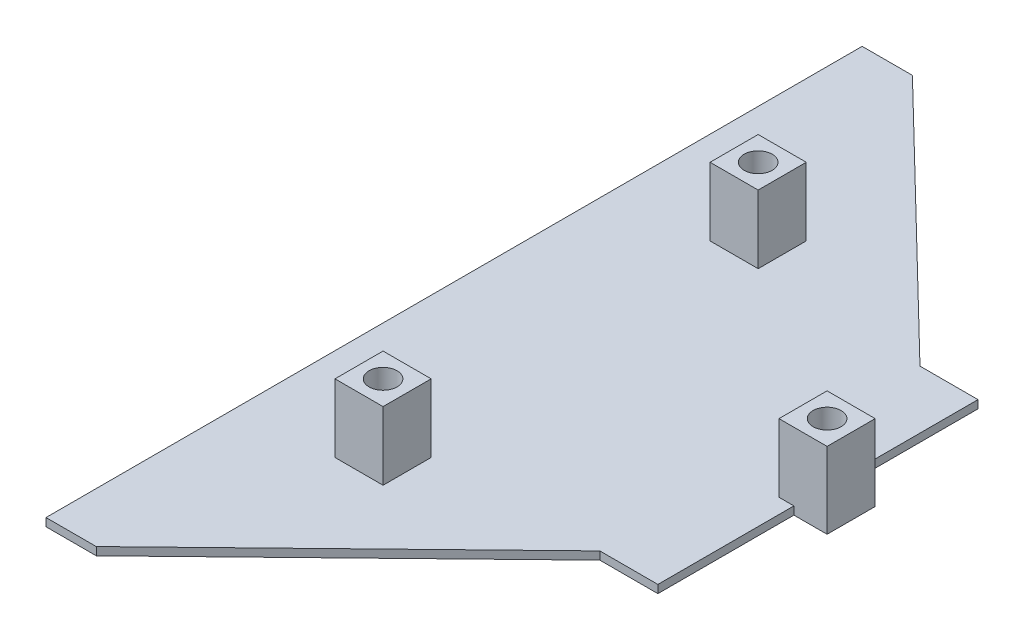
SolidWorks part; units mm, degrees
ref_plane "Front Plane" through (0, 0, 0) normal (0, 0, 1) x (1, 0, 0)
ref_plane "Top Plane" through (0, 0, 0) normal (0, 1, 0) x (1, 0, 0)
ref_plane "Right Plane" through (0, 0, 0) normal (1, 0, 0) x (0, 0, -1)
sketch "Croquis1" plane through (0, 0, 0) normal (0, 1, 0) x (1, 0, 0)
  line L0 (0, 0) -> (0, -101.83)
  line L1 (0, -101.83) -> (6.27, -101.83)
  line L3 (6.27, -101.83) -> (38.16, -70.885)
  line L4 (38.16, -70.885) -> (45.4, -70.885)
  line L5 (45.4, -70.885) -> (45.4, -30.945)
  line L6 (45.4, -30.945) -> (38.16, -30.945)
  line L7 (38.16, -30.945) -> (6.27, 0)
  line L9 (6.27, 0) -> (0, 0)
  point P12 (45.4, -50.915)
  point P13 (0, -50.915)
  dimension "D1" = 6.27
  dimension "D2" = 101.83
  dimension "D3" = 45.4
  dimension "D5" = 7.24
  dimension "D6" = 39.94
extrude "Saliente-Extruir1" add sketch "Croquis1" along normal blind 1
sketch "Croquis2" plane through (0, 1, 0) normal (0, 1, 0) x (1, 0, 0)
  line L0 (45.4, -70.885) -> (45.4, -30.945) construction
  line L2 (11.54, -24.515) -> (17.54, -24.515)
  line L3 (11.54, -24.515) -> (11.54, -30.515)
  line L4 (11.54, -30.515) -> (17.54, -30.515)
  line L5 (17.54, -24.515) -> (17.54, -30.515)
  line L6 (11.54, -24.515) -> (17.54, -30.515) construction
  line L7 (11.54, -30.515) -> (17.54, -24.515) construction
  line L8 (11.54, -71.315) -> (17.54, -71.315)
  line L9 (11.54, -71.315) -> (11.54, -77.315)
  line L10 (11.54, -77.315) -> (17.54, -77.315)
  line L11 (17.54, -71.315) -> (17.54, -77.315)
  line L12 (11.54, -71.315) -> (17.54, -77.315) construction
  line L13 (11.54, -77.315) -> (17.54, -71.315) construction
  line L14 (43.54, -47.915) -> (49.54, -47.915)
  line L15 (43.54, -47.915) -> (43.54, -53.915)
  line L16 (43.54, -53.915) -> (49.54, -53.915)
  line L17 (49.54, -47.915) -> (49.54, -53.915)
  line L18 (43.54, -47.915) -> (49.54, -53.915) construction
  line L19 (43.54, -53.915) -> (49.54, -47.915) construction
  circle A0 centre (14.54, -74.315) radius 1.75
  circle A1 centre (14.54, -27.515) radius 1.75
  circle A2 centre (46.54, -50.915) radius 1.75
  point P6 (45.4, -50.915)
  dimension "D4" = 3.5
  dimension "D1" = 46.8
  dimension "D2" = 23.4
  dimension "D3" = 30.86
  dimension "D5" = 6
  dimension "D6" = 6
  dimension "D7" = 6
  dimension "D8" = 6
  dimension "D9" = 32
  dimension "D10" = 6
  dimension "D11" = 6
extrude "Saliente-Extruir2" add sketch "Croquis2" along normal blind 8.5
sketch "Croquis3" plane through (0, 1, 0) normal (0, -1, 0) x (1, 0, 0)
  line L1 (49.54, 47.915) -> (45.4, 47.915)
  line L2 (49.54, 47.915) -> (49.54, 53.915)
  line L3 (49.54, 53.915) -> (45.4, 53.915)
  line L4 (45.4, 47.915) -> (45.4, 53.915)
extrude "Saliente-Extruir3" add sketch "Croquis3" along normal up to surface (1 mm away) up to face at (22.4575, 0, 50.915)
equation "\"D2@Croquis2\"=\"D1@Croquis2\"/2"
